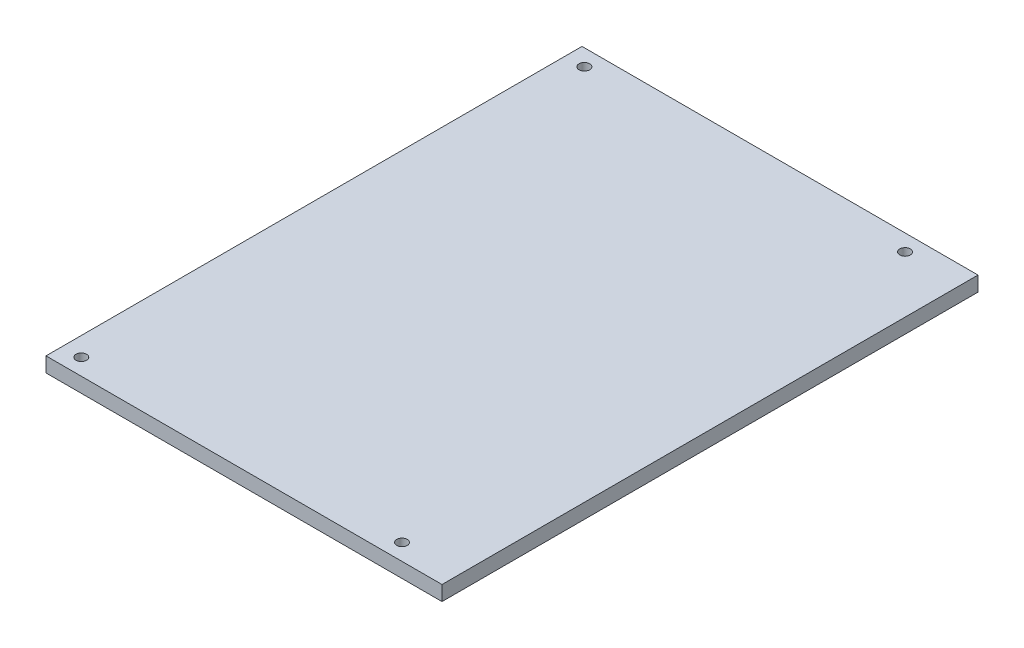
SolidWorks part; units mm, degrees
ref_plane "前视" through (0, 0, 0) normal (0, 0, 1) x (1, 0, 0)
ref_plane "上视" through (0, 0, 0) normal (0, 1, 0) x (1, 0, 0)
ref_plane "右视" through (0, 0, 0) normal (1, 0, 0) x (0, 0, -1)
sketch "Sketch1" plane through (0, 0, 0) normal (0, 1, 0) x (1, 0, 0)
  line L1 (-139.5587, 165.8917) -> (127.6613, 165.8917)
  line L2 (-139.5587, 165.8917) -> (-139.5587, -195.7883)
  line L3 (-139.5587, -195.7883) -> (127.6613, -195.7883)
  line L4 (127.6613, 165.8917) -> (127.6613, -195.7883)
  circle A0 centre (-126.8587, -184.6758) radius 3.57
  circle A1 centre (-126.8587, 154.7792) radius 3.57
  circle A2 centre (89.5613, 154.7792) radius 3.57
  circle A3 centre (89.5613, -184.6758) radius 3.57
  point P4 (-126.8587, -184.6758)
  point P7 (89.5613, -184.6758)
  point P8 (89.5613, 154.7792)
  point P9 (-126.8587, 154.7792)
  dimension "D5" = 38.1
  dimension "D7" = 216.42
  dimension "D1" = 267.22
  dimension "D2" = 361.68
  dimension "D3" = 11.1125
  dimension "D4" = 12.7
  dimension "D6" = 11.1125
  dimension "D8" = 38.1
  dimension "D9" = 11.1125
  dimension "D10" = 12.7
extrude "Boss-Extrude1" add sketch "Sketch1" along normal blind 10
